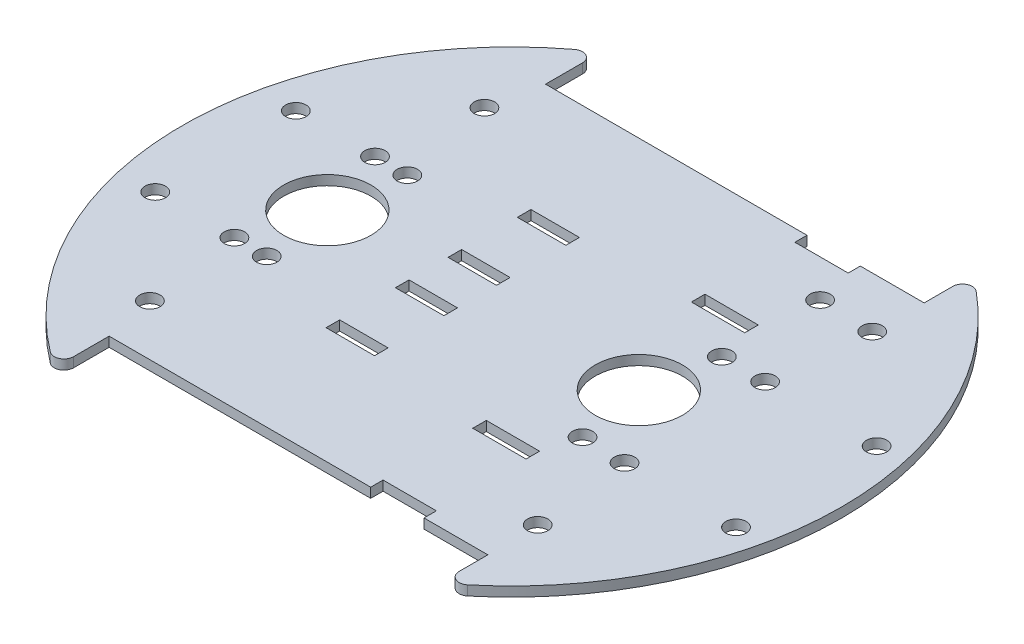
SolidWorks part; units mm, degrees
ref_plane "Front Plane" through (0, 0, 0) normal (0, 0, 1) x (1, 0, 0)
ref_plane "Top Plane" through (0, 0, 0) normal (0, 1, 0) x (1, 0, 0)
ref_plane "Right Plane" through (0, 0, 0) normal (1, 0, 0) x (0, 0, -1)
sketch "Sketch1" plane through (0, 0, 0) normal (0, 1, 0) x (1, 0, 0)
  line L2 (-37.9002, -45.0137) -> (-37.9002, -56.2205)
  line L7 (27.0557, 44.9863) -> (40.2239, 44.9863)
  line L8 (16.0557, -45.0137) -> (-37.9002, -45.0137)
  line L10 (16.0557, -42.4656) -> (27.0557, -42.4656)
  line L11 (27.0557, -42.4656) -> (27.0557, -45.0137)
  line L12 (16.0557, -45.0137) -> (16.0557, -42.4656)
  line L13 (27.0557, -45.0137) -> (40.2239, -45.0137)
  line L14 (27.0557, 42.4863) -> (27.0557, 44.9863)
  line L15 (16.0557, 42.4863) -> (27.0557, 42.4863)
  line L16 (16.0557, 44.9863) -> (16.0557, 42.4863)
  line L17 (16.0557, 44.9863) -> (-37.9002, 45.0137)
  line L26 (40.2239, 44.9863) -> (40.2239, 54.9863)
  line L27 (40.2239, -45.0137) -> (40.2239, -55.0137)
  line L31 (-37.9002, 56.5088) -> (-37.9002, 45.0137)
  line L55 (-17.0204, 21.1198) -> (-17.0194, 18.3198)
  line L56 (-17.0204, 21.1198) -> (-7.0204, 21.1232)
  line L57 (16.0557, -23.9656) -> (27.0557, -23.9656)
  line L58 (16.0557, -23.9656) -> (16.0557, -21.1656)
  line L59 (-7.0204, 21.1232) -> (-7.0194, 18.3232)
  line L60 (-17.0194, 18.3198) -> (-7.0194, 18.3232)
  line L63 (27.0557, -23.9656) -> (27.0557, -21.1656)
  line L64 (16.0557, -21.1656) -> (27.0557, -21.1656)
  line L65 (16.0557, 23.9381) -> (27.0557, 23.9381)
  line L66 (27.0557, 23.9381) -> (27.0557, 21.1381)
  line L67 (16.0557, 21.1381) -> (27.0557, 21.1381)
  line L68 (16.0557, 23.9381) -> (16.0557, 21.1381)
  line L80 (-17.0221, -4.0307) -> (-17.0223, -6.8307)
  line L81 (-17.0223, -6.8307) -> (-7.0223, -6.8315)
  line L82 (-17.0204, 4.0232) -> (-7.0204, 4.0198)
  line L83 (-7.0204, 4.0198) -> (-7.0194, 6.8198)
  line L84 (-17.0194, 6.8232) -> (-7.0194, 6.8198)
  line L85 (-17.0204, 4.0232) -> (-17.0194, 6.8232)
  line L86 (-7.0221, -4.0315) -> (-7.0223, -6.8315)
  line L87 (-17.0221, -4.0307) -> (-7.0221, -4.0315)
  line L88 (-17.0294, -21.1272) -> (-7.0294, -21.135)
  line L89 (-7.0294, -21.135) -> (-7.0272, -18.335)
  line L90 (-17.0272, -18.3272) -> (-7.0272, -18.335)
  line L91 (-17.0294, -21.1272) -> (-17.0272, -18.3272)
  circle A7 centre (40.0046, -34.516) radius 2.1
  circle A8 centre (40.0002, 34.5) radius 2.1
  circle A9 centre (37.9002, -14.5) radius 2.1
  circle A10 centre (37.9002, 14.5) radius 2.1
  circle A11 centre (60.9002, 14.5) radius 2.1
  circle A12 centre (60.9002, -14.5) radius 2.1
  circle A13 centre (-40.0002, -34.5) radius 2.1
  circle A14 centre (-35.9002, -14.5) radius 2.1
  circle A15 centre (-58.9002, -14.5) radius 2.1
  circle A16 centre (-58.9002, 14.5) radius 2.1
  circle A17 centre (-35.9002, 14.5) radius 2.1
  circle A18 centre (-40.0002, 34.5) radius 2.1
  arc A19 (40.2239, 54.9863) -> (40.2239, -55.0137) centre (0.0693, -0.0137) cw
  arc A20 (-37.9002, 56.5088) -> (-37.9002, -56.2205) centre (-0.1174, 0.1441) ccw
  circle A21 centre (26.3664, -0.0137) radius 9
  circle A22 centre (-37.9002, 0) radius 9
  circle A23 centre (28.9738, -14.2342) radius 2.1
  circle A24 centre (28.9738, 14.5) radius 2.1
  circle A25 centre (28.9738, 34.7702) radius 2.1
  circle A26 centre (-42.5688, -14.5) radius 2.1
  circle A27 centre (-42.5688, 14.5) radius 2.1
  point P3 (0, 0)
  point P6 (40.0002, -0.0137)
  point P9 (0, 0)
  point P14 (0, 45)
  point P61 (0.0693, -0.0137)
  point P72 (-67.974, 0.1441)
  point P73 (68.1677, -0.0137)
  dimension "D6" = 4.2
  dimension "D7" = 10
  dimension "D9" = 18.5
  dimension "D11" = 29
  dimension "D13" = 4.2
  dimension "D5" = 4.2
  dimension "D20" = 136.1416
  dimension "D8" = 4.2
  dimension "D10" = 4.2
  dimension "D21" = 4.2
  dimension "D14" = 23
  dimension "D15" = 23
  dimension "D2" = 110
  dimension "D3" = 10
  dimension "D4" = 23
  dimension "D12" = 10.5
  dimension "D16" = 11
  dimension "D17" = 11
  dimension "D18" = 2.5482
  dimension "D19" = 2.8
extrude "Boss-Extrude2" add sketch "Sketch1" along normal blind 2
fillet "Fillet2" radius 2 1 edges at (-37.9002, 1, -56.5088)
fillet "Fillet3" radius 2 1 edges at (40.2239, 1, -54.9863)
fillet "Fillet4" radius 2 1 edges at (40.2239, 1, 55.0137)
fillet "Fillet5" radius 2 1 edges at (-37.9002, 1, 56.2205)
